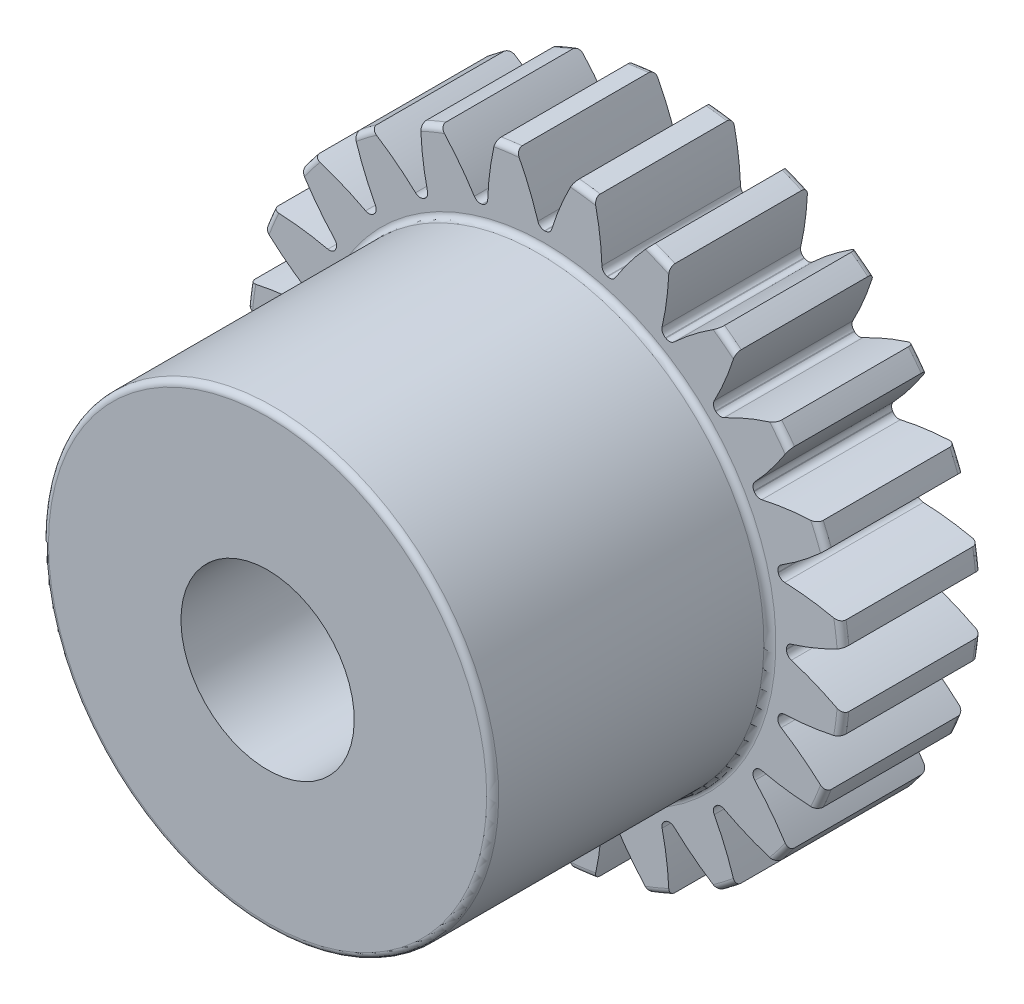
SolidWorks part; units mm, degrees
ref_plane "Front Plane" through (0, 0, 0) normal (0, 0, 1) x (1, 0, 0)
ref_plane "Top Plane" through (0, 0, 0) normal (0, 1, 0) x (1, 0, 0)
ref_plane "Right Plane" through (0, 0, 0) normal (1, 0, 0) x (0, 0, -1)
sketch "Sketch1" plane through (0, 0, 0) normal (0, 0, 1) x (1, 0, 0)
  line L0 (-304.8, 0) -> (304.8, 0) construction
  circle A0 centre (0, 0) radius 6.858 construction
  circle A1 centre (0, 0) radius 6.35 construction
  circle A2 centre (0, 0) radius 5.5351 construction
  circle A3 centre (0, 0) radius 5.1562 construction
  circle A4 centre (0, 0) radius 1.9844 construction
  dimension "D2" = 0.508
  dimension "D3" = 1.3229
  dimension "D1" = 1.3229
sketch "Sketch2" plane through (0, 0, 0) normal (1, 0, 0) x (0, 0, -1)
  line L0 (0, 0) -> (-3.175, 0) construction
  line L1 (-3.175, 0) -> (-9.525, 0) construction
  dimension "Overall Width" = 9.525
  dimension "Face Width" = 3.175
sketch "Sketch4" plane through (0, 0, 0) normal (1, 0, 0) x (0, 0, -1)
  line L0 (-9.525, 1.9844) -> (-9.525, 5.1562)
  line L1 (-9.525, 5.1562) -> (-3.175, 5.1562)
  line L2 (-3.175, 5.1562) -> (-3.175, 6.858)
  line L3 (-3.175, 6.858) -> (0, 6.858)
  line L4 (0, 6.858) -> (0, 1.9844)
  line L5 (-3.175, 5.1562) -> (-3.175, 0) construction
  line L6 (0, 6.858) -> (0, -6.858) construction
  line L7 (-3.175, 5.1562) -> (0, 5.1562) construction
  line L12 (-9.525, 1.9844) -> (0, 1.9844)
revolve "Revolve1" add sketch "Sketch4" angle 360 about L1
fillet "Fillet2" radius 0.1372 4 edges at (0, 5.1562, 9.525) (0, 5.1562, 3.175) (0, 6.858, 3.175) (0, 6.858, 0)
sketch "Sketch7" plane through (0, 0, 3.175) normal (0, 0, 1) x (1, 0, 0)
  line L0 (0, 0) -> (0, 6.858) construction
  line L1 (0.4153, 6.3364) -> (0.632, 6.8288) construction
  line L3 (0.8951, 6.7993) -> (0.8288, 6.2957) construction
  line L4 (0.8288, 6.2957) -> (0.7225, 5.4877) construction
  line L5 (0, 0) -> (0.7225, 5.4877) construction
  line L6 (0.4153, 6.3364) -> (0, 0) construction
  line L7 (0.4153, 6.3364) -> (0.4485, 6.8433) construction
  line L8 (0.4153, 6.3364) -> (0, 0) construction
  circle A0 centre (0, 0) radius 6.858 construction
  arc A1 (-0.0066, 5.5351) -> (0.0066, 5.5351) centre (0, 0) cw
  circle A2 centre (0, 0) radius 5.5351 construction
  arc A3 (-0.4153, 6.3364) -> (0.4153, 6.3364) centre (0, 0) cw construction
  circle A4 centre (0, 0) radius 6.35 construction
  arc A5 (1.1326, 6.7638) -> (0.6566, 6.8265) centre (0, 0) ccw construction
  arc A6 (0.4153, 6.3364) -> (1.2388, 6.228) centre (0, 0) cw construction
  arc A7 (-0.6566, 6.8265) -> (0.6566, 6.8265) centre (0, 0) cw
  arc A8 (0.1586, 5.6471) -> (0.6566, 6.8265) centre (6.2275, 3.779) cw
  arc A9 (-0.1586, 5.6471) -> (-0.6566, 6.8265) centre (-6.2275, 3.779) ccw
  arc A10 (-0.0066, 5.5351) -> (-0.1586, 5.6471) centre (-0.0068, 5.6938) cw
  arc A11 (0.0066, 5.5351) -> (0.1586, 5.6471) centre (0.0068, 5.6938) ccw
  point P26 (-0.1248, 5.5337)
  point P29 (0.1248, 5.5337)
  dimension "D4" = 0.1588
  dimension "D5" = 6.35
  dimension "D3" = 20
  dimension "D1" = 1.6624
  dimension "D2" = 0.8312
extrude "Cut-Extrude2" cut sketch "Sketch7" against normal through all
pattern_circular "CirPattern1" count 24 over 360 about axis through (0, 0, 0) along (0, 0, 1) of "Cut-Extrude2"
equation "\"D1@Sketch1\"=2.5*(\"Pitch Dia.@Sketch1\"/\"Number of Teeth@Sketch1\")"
equation "\"D1@CirPattern1\"=\"Number of Teeth@Sketch1\""
equation "\"D1@Fillet2\"=\"OD@Sketch1\"*.01"
equation "\"D1@Sketch7\"=3.14159*(\"Pitch Dia.@Sketch1\"/\"Number of Teeth@Sketch1\")"
equation "\"D2@Sketch7\"=\"D1@Sketch7\"/2"
equation "\"D4@Sketch7\"=\"D1@Sketch7\"*.0955"
equation "\"D5@Sketch7\"=\"Pitch Dia.@Sketch1\"/2"
